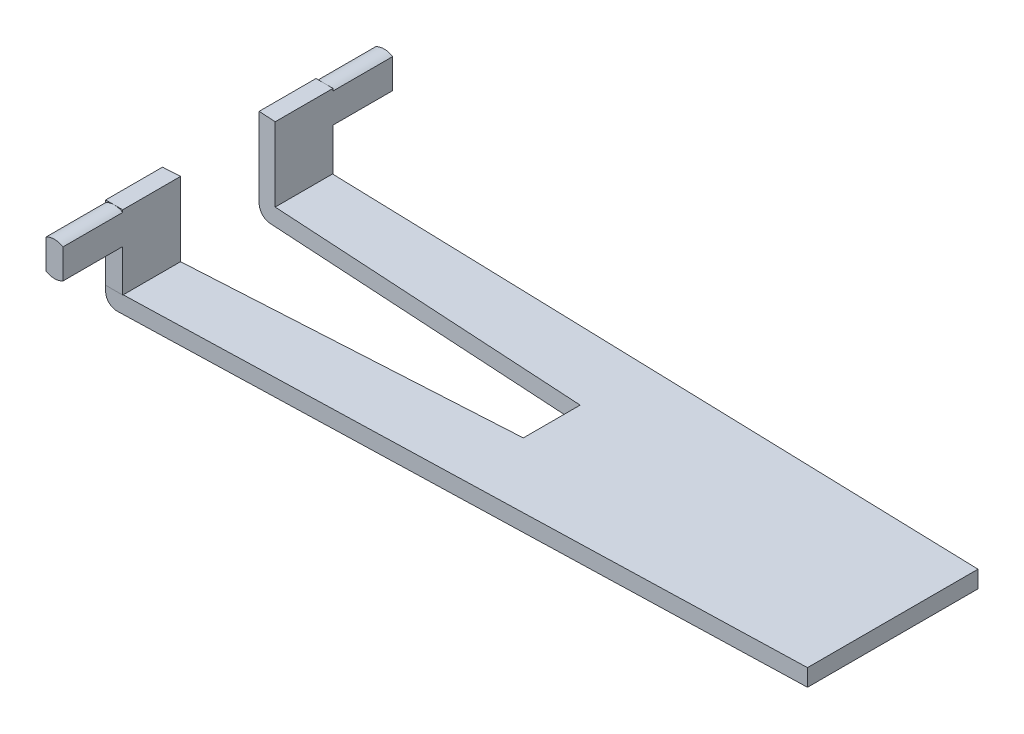
SolidWorks part; units mm, degrees
ref_plane "Front Plane" through (0, 0, 0) normal (0, 0, 1) x (1, 0, 0)
ref_plane "Top Plane" through (0, 0, 0) normal (0, 1, 0) x (1, 0, 0)
ref_plane "Right Plane" through (0, 0, 0) normal (1, 0, 0) x (0, 0, -1)
sketch "Sketch1" plane through (0, 0, 0) normal (0, 1, 0) x (1, 0, 0)
  line L0 (-6, 1.8524) -> (6, 1.5)
  line L1 (0, 0) -> (-6, 0.0024) construction
  line L2 (6, -1.5) -> (6, 1.5)
  line L3 (-6, 0.8524) -> (0, 0.5)
  line L4 (-6, -1.8476) -> (-6, -0.8476)
  line L5 (0, 0.5) -> (0, -0.5)
  line L6 (0, -0.5) -> (-6, -0.8476)
  line L7 (-6, -1.8476) -> (6, -1.5)
  line L8 (0, 0) -> (6, 0) construction
  line L9 (-6, 0.8524) -> (-6, 1.8524)
  point P0 (0, 0)
  dimension "D1" = 3.7
  dimension "D2" = 6
  dimension "D3" = 1.5
  dimension "D4" = 1.85
  dimension "D6" = 1
  dimension "D7" = 1
  dimension "D8" = 12
  dimension "D9" = 0.5
  dimension "D10" = 1
extrude "Boss-Extrude1" add sketch "Sketch1" along normal blind 0.3
sketch "Sketch2" plane through (0, 0.3, 0) normal (0, 1, 0) x (1, 0, 0)
  line L0 (-6, 0.8524) -> (-6, 2.9024)
  line L1 (-6, 2.9024) -> (-5.7, 2.9024)
  line L2 (-5.7, 2.9024) -> (-5.7, 0.8347)
  line L3 (-6, 0.8524) -> (0, 0.5) construction
  line L4 (-5.7, 0.8347) -> (-6, 0.8524)
  line L5 (-6, -0.8476) -> (-6, -2.8976)
  line L6 (-6, -2.8976) -> (-5.7, -2.8976)
  line L7 (-5.7, -2.8976) -> (-5.7, -0.8303)
  line L8 (0, -0.5) -> (-6, -0.8476) construction
  line L9 (-5.7, -0.8303) -> (-6, -0.8476)
  dimension "D1" = 0.3
  dimension "D2" = 1.05
  dimension "D3" = 1.05
  dimension "D4" = 0.3
extrude "Boss-Extrude2" add sketch "Sketch2" along normal blind 1.3
sketch "Sketch3" plane through (-6, 0, 0) normal (-1, 0, 0) x (0, 0, 1)
  line L0 (-1.8524, 0.3) -> (-1.8524, 1)
  line L1 (-1.8524, 1) -> (-2.9024, 1)
  line L2 (-2.9024, 1.6) -> (-2.9024, 0.3) construction
  line L3 (-2.9024, 1) -> (-2.9024, 0.3)
  line L4 (-2.9024, 0.3) -> (-1.8524, 0.3)
  line L5 (1.8476, 0.3) -> (1.8476, 1)
  line L6 (1.8476, 1) -> (2.8976, 1)
  line L7 (2.8976, 1.6) -> (2.8976, 0.3) construction
  line L8 (2.8976, 1) -> (2.8976, 0.3)
  line L9 (2.8976, 0.3) -> (1.8476, 0.3)
  line L10 (-2.9024, 1.6) -> (-0.8524, 1.6) construction
  line L11 (0.8476, 1.6) -> (2.8976, 1.6) construction
  dimension "D1" = 0.6
  dimension "D2" = 0.6
extrude "Cut-Extrude1" cut sketch "Sketch3" against normal blind 0.3
fillet "Fillet1" radius 0.2 2 edges at (-6, 0, 1.3476) (-6, 0, -1.3524)
sketch "Sketch4" plane through (0, 0, -2.9024) normal (0, 0, -1) x (-1, 0, 0)
  line L0 (5.7, 1.6) -> (6, 1) construction
  line L1 (6, 1) -> (5.7, 1) construction
  line L2 (5.7, 1) -> (6, 1.6) construction
  line L3 (5.7, 1.5598) -> (5.7, 1.0402)
  line L4 (5.7, 1.6) -> (5.7, 1) construction
  line L5 (6, 1.5598) -> (6, 1.0402)
  line L6 (6, 1.6) -> (6, 1) construction
  arc A0 (5.7, 1.0402) -> (6, 1.0402) centre (5.85, 1.3) ccw
  arc A1 (6, 1.5598) -> (5.7, 1.5598) centre (5.85, 1.3) ccw
extrude "Cut-Extrude3" cut sketch "Sketch4" against normal blind 1.05 flip side to cut
sketch "Sketch5" plane through (0, 0, 2.8976) normal (0, 0, 1) x (1, 0, 0)
  line L0 (-6, 1.6) -> (-5.7, 1) construction
  line L1 (-6, 1) -> (-5.7, 1.6) construction
  line L2 (-5.7, 1.5598) -> (-5.7, 1.0402)
  line L3 (-6, 1.5598) -> (-6, 1.0402)
  arc A0 (-5.7, 1.5598) -> (-6, 1.5598) centre (-5.85, 1.3) ccw
  arc A1 (-6, 1.0402) -> (-5.7, 1.0402) centre (-5.85, 1.3) ccw
extrude "Cut-Extrude4" cut sketch "Sketch5" against normal blind 1.05 flip side to cut
